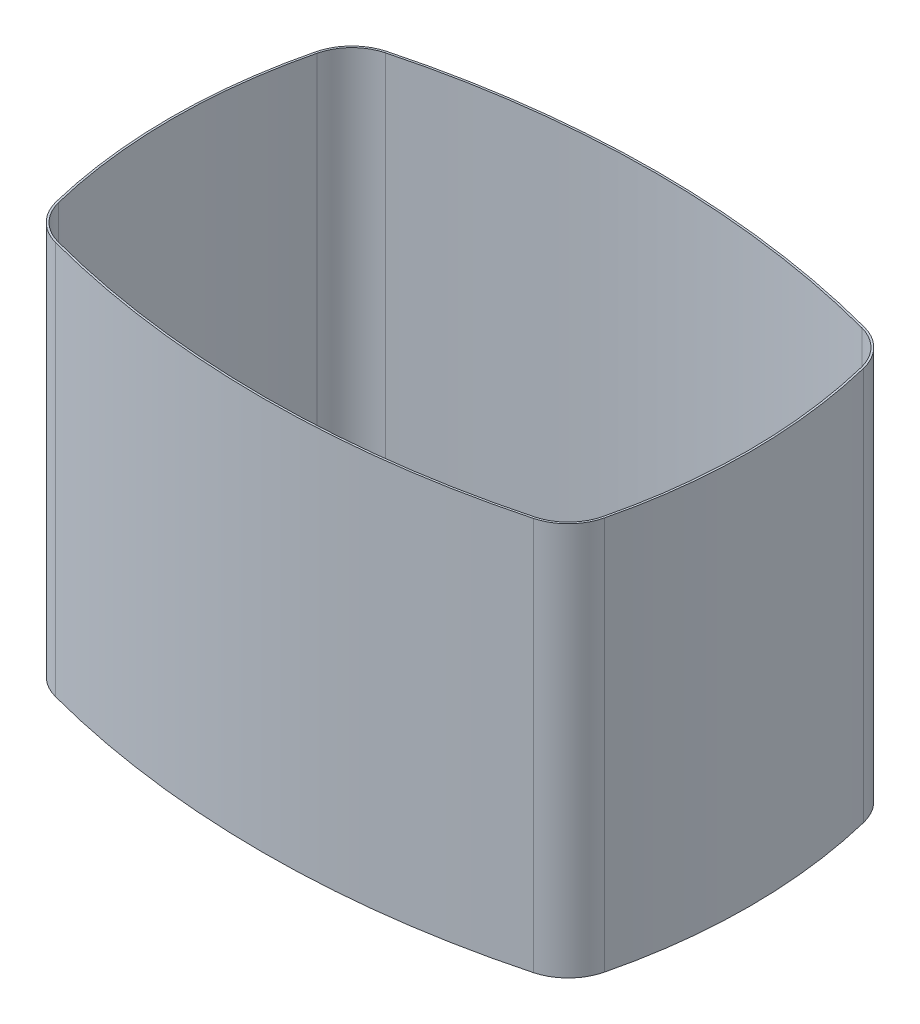
SolidWorks part; units mm, degrees
ref_plane "Front Plane" through (0, 0, 0) normal (0, 0, 1) x (1, 0, 0)
ref_plane "Top Plane" through (0, 0, 0) normal (0, 1, 0) x (1, 0, 0)
ref_plane "Right Plane" through (0, 0, 0) normal (1, 0, 0) x (0, 0, -1)
sketch "Sketch1" plane through (0, 0, 0) normal (0, 1, 0) x (1, 0, 0)
  arc A0 (-121.4098, 84.1643) -> (-139.283, 65.9442) centre (-115, 60) ccw
  arc A1 (121.4098, 84.1643) -> (139.283, 65.9442) centre (115, 60) cw
  arc A4 (-121.4098, 84.1643) -> (121.4098, 84.1643) centre (0, -373.5422) cw
  arc A5 (-139.283, 65.9442) -> (-139.283, -65.9442) centre (130.1091, 0) ccw
  arc A6 (-121.4098, -84.1643) -> (121.4098, -84.1643) centre (0, 373.5422) ccw
  arc A7 (139.283, 65.9442) -> (139.283, -65.9442) centre (-130.1091, 0) cw
  arc A8 (-121.4098, -84.1643) -> (-139.283, -65.9442) centre (-115, -60) cw
  arc A9 (121.4098, -84.1643) -> (139.283, -65.9442) centre (115, -60) ccw
  point P0 (0, 0)
  dimension "D3" = 50
  dimension "D4" = 473.5352
  dimension "D1" = 120
  dimension "D2" = 230
extrude "Boss-Extrude1" add sketch "Sketch1" along normal blind 200
sketch "Sketch2" plane through (0, 0, 0) normal (0, 0, 1) x (1, 0, 0)
  line L0 (0, 0) -> (0, 309.5969) construction
  line L1 (174.434, 453.9235) -> (100, 325)
  line L2 (121.4098, 200) -> (-121.4098, 200) construction
  dimension "D1" = 125
  dimension "D2" = 100
  dimension "D3" = 30
shell "Shell3" thickness 1
sketch "Sketch3" plane through (0, 0, 0) normal (0, -1, 0) x (1, 0, 0)
  arc A16 (-121.1534, -83.1978) -> (121.1534, -83.1978) centre (0, 373.5422) ccw
  arc A17 (121.1534, -83.1978) -> (138.3117, -65.7065) centre (115, -60) ccw
  arc A18 (138.3117, -65.7065) -> (138.3117, 65.7065) centre (-130.1091, 0) ccw
  arc A19 (138.3117, 65.7065) -> (121.1534, 83.1978) centre (115, 60) ccw
  arc A20 (121.1534, 83.1978) -> (-121.1534, 83.1978) centre (0, -373.5422) ccw
  arc A21 (-121.1534, 83.1978) -> (-138.3117, 65.7065) centre (-115, 60) ccw
  arc A22 (-138.3117, 65.7065) -> (-138.3117, -65.7065) centre (130.1091, 0) ccw
  arc A23 (-138.3117, -65.7065) -> (-121.1534, -83.1978) centre (-115, -60) ccw
  arc A24 (-121.1534, -83.1978) -> (121.1534, -83.1978) centre (0, 373.5422) ccw
  arc A25 (121.1534, -83.1978) -> (138.3117, -65.7065) centre (115, -60) ccw
  arc A26 (138.3117, -65.7065) -> (138.3117, 65.7065) centre (-130.1091, 0) ccw
  arc A27 (138.3117, 65.7065) -> (121.1534, 83.1978) centre (115, 60) ccw
  arc A28 (121.1534, 83.1978) -> (-121.1534, 83.1978) centre (0, -373.5422) ccw
  arc A29 (-121.1534, 83.1978) -> (-138.3117, 65.7065) centre (-115, 60) ccw
  arc A30 (-138.3117, 65.7065) -> (-138.3117, -65.7065) centre (130.1091, 0) ccw
  arc A31 (-138.3117, -65.7065) -> (-121.1534, -83.1978) centre (-115, -60) ccw
  dimension "D1" = 1
extrude "Cut-Extrude1" cut sketch "Sketch3" against normal blind 200
ref_plane "Plane1" through (100, 325, 0) normal (-0.5, -0.866, 0) x (-0.866, 0.5, 0)
sketch "Sketch5" plane through (100, 325, 0) normal (-0.5, -0.866, 0) x (-0.866, 0.5, 0)
  circle A0 centre (1.0012, 0) radius 30
  dimension "D1" = 60
sketch "Sketch7" plane through (0, 0, 0) normal (0, 0, 1) x (1, 0, 0)
  spline S0 degree 2 poles (72.0535, 316.1407) (-121.918, 286.5068) (-118.0931, 164.9383) knots 0 0 0 1 1 1
  point P2 (92.4846, 313.9853)
  point P4 (94.4834, 317.4473)
  point P5 (72.0535, 316.1407)
